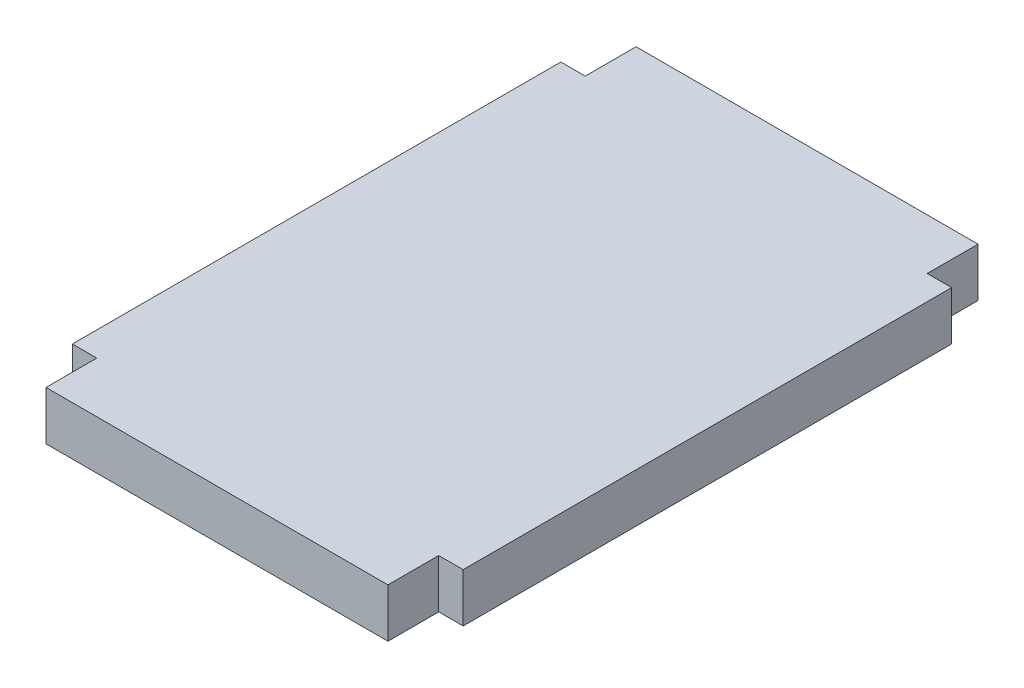
SolidWorks part; units mm, degrees
ref_plane "Front Plane" through (0, 0, 0) normal (0, 0, 1) x (1, 0, 0)
ref_plane "Top Plane" through (0, 0, 0) normal (0, 1, 0) x (1, 0, 0)
ref_plane "Right Plane" through (0, 0, 0) normal (1, 0, 0) x (0, 0, -1)
sketch "Sketch2" plane through (0, 0, 0) normal (0, 1, 0) x (1, 0, 0)
  line L0 (-22.225, 31.75) -> (-22.225, 38.354)
  line L1 (-25.4, 31.75) -> (-22.225, 31.75)
  line L2 (-25.4, 31.75) -> (-25.4, -31.75)
  line L3 (-25.4, -31.75) -> (-22.225, -31.75)
  line L4 (25.4, 31.75) -> (25.4, -31.75)
  line L5 (-25.4, 31.75) -> (25.4, -31.75) construction
  line L6 (-25.4, -31.75) -> (25.4, 31.75) construction
  line L7 (-22.225, 38.354) -> (22.225, 38.354)
  line L8 (22.225, 38.354) -> (22.225, 31.75)
  line L9 (0, -17.1577) -> (0, 22.8776) construction
  line L10 (22.225, 31.75) -> (25.4, 31.75)
  line L11 (-18.7096, 0) -> (22.3816, 0) construction
  line L12 (22.225, -38.354) -> (22.225, -31.75)
  line L13 (-22.225, -38.354) -> (22.225, -38.354)
  line L14 (-22.225, -31.75) -> (-22.225, -38.354)
  line L15 (22.225, -31.75) -> (25.4, -31.75)
  point P0 (0, 0)
  point P12 (0, 38.354)
  dimension "D1" = 63.5
  dimension "D2" = 50.8
  dimension "D3" = 6.604
  dimension "D4" = 44.45
extrude "Boss-Extrude1" add sketch "Sketch2" along normal blind 6.35
